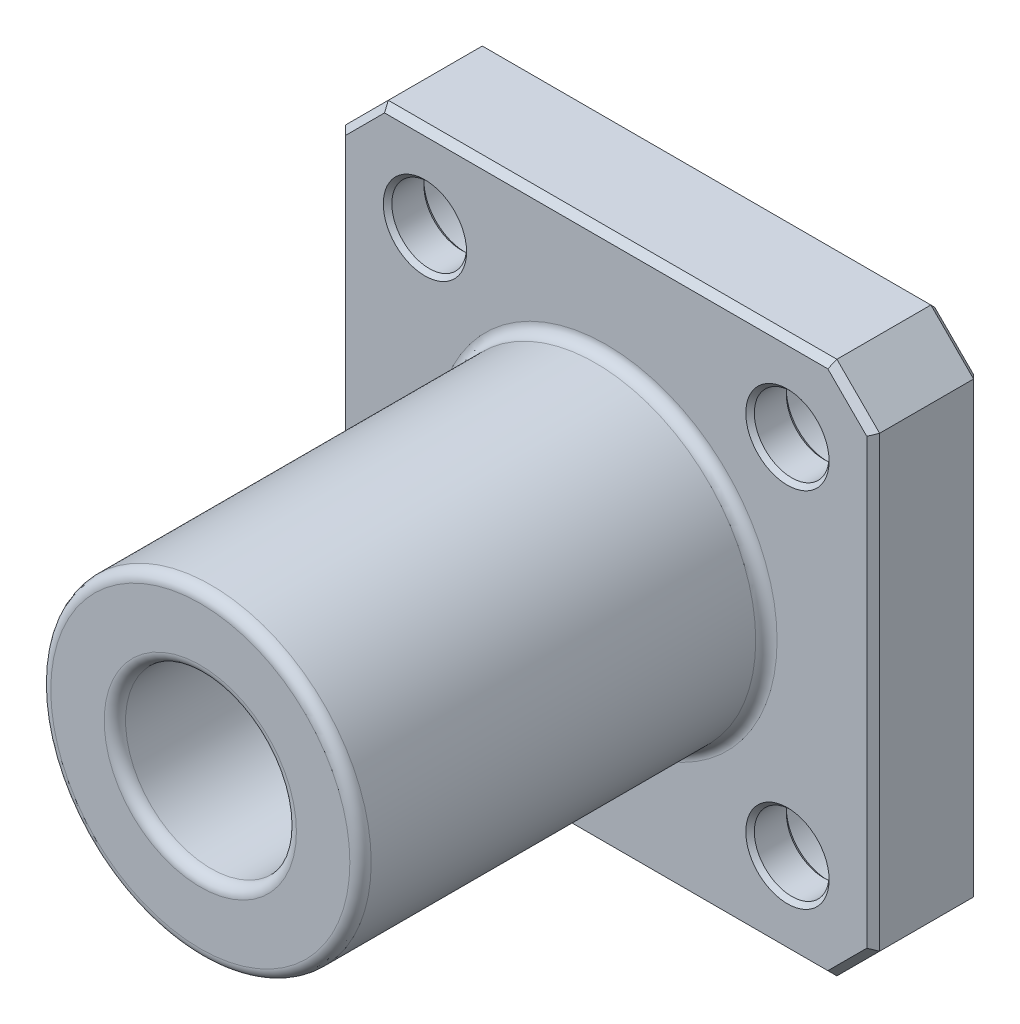
SolidWorks part; units mm, degrees
ref_plane "前视基准面" through (0, 0, 0) normal (0, 0, 1) x (1, 0, 0)
ref_plane "上视基准面" through (0, 0, 0) normal (0, 1, 0) x (1, 0, 0)
ref_plane "右视基准面" through (0, 0, 0) normal (1, 0, 0) x (0, 0, -1)
sketch "Sketch1" plane through (0, 0, 0) normal (0, 0, 1) x (1, 0, 0)
  line L1 (-12.5, 12.5) -> (12.5, 12.5)
  line L2 (-12.5, 12.5) -> (-12.5, -12.5)
  line L3 (-12.5, -12.5) -> (12.5, -12.5)
  line L4 (12.5, 12.5) -> (12.5, -12.5)
  line L5 (-12.5, 12.5) -> (12.5, -12.5) construction
  line L6 (-12.5, -12.5) -> (12.5, 12.5) construction
  circle A0 centre (0, 0) radius 4
  point P0 (0, 0)
  dimension "D2" = 8
  dimension "D1" = 25
extrude "Boss-Extrude1" add sketch "Sketch1" along normal blind 5
sketch "Sketch2" plane through (0, 0, 5) normal (0, 0, 1) x (1, 0, 0)
  circle A0 centre (0, 0) radius 7.5
  circle A1 centre (0, 0) radius 4
  dimension "D1" = 15
extrude "Boss-Extrude2" add sketch "Sketch2" along normal blind 19
chamfer "Chamfer1" distance 2 angle 45 4 edges at (-12.5, 12.5, 2.5) (-12.5, -12.5, 2.5) (12.5, -12.5, 2.5) (12.5, 12.5, 2.5)
sketch "Sketch3" plane through (0, 0, 0) normal (0, 0, -1) x (-1, 0, 0)
  line L0 (0, 0) -> (-11.5, 11.5) construction
  line L1 (-10.5, 12.5) -> (-12.5, 10.5) construction
  circle A0 centre (0, 0) radius 12 construction
  circle A1 centre (-8.4853, 8.4853) radius 1.5
  circle A2 centre (8.4853, 8.4853) radius 1.5
  circle A3 centre (8.4853, -8.4853) radius 1.5
  circle A4 centre (-8.4853, -8.4853) radius 1.5
  point P17 (0, 0)
  dimension "D1" = 24
  dimension "D2" = 3
  dimension "D3" = 4
hole_wizard "CBORE for M3 Pan Head Screw1" positions "3DSketch1" profile "Sketch4" counterbore size "M3" standard "JIS" end condition through all
sketch3d "3DSketch1"
  point P0 (8.4853, 8.4853, 0)
  point P3 (-8.4853, 8.4853, 0)
  point P6 (-8.4853, -8.4853, 0)
  point P9 (8.4853, -8.4853, 0)
sketch "Sketch4" plane through (8.4853, 8.4853, 0) normal (1, 0, 0) x (0, 1, 0)
  line L0 (0, 0) -> (0, 24)
  line L1 (0, 24) -> (1.75, 24)
  line L3 (1.75, 24) -> (1.75, 3.1)
  line L4 (3, 3.1) -> (1.75, 3.1)
  line L5 (3, 3.1) -> (3, 0.525)
  line L6 (3, 0.525) -> (3.525, 0)
  line L7 (3.525, 0) -> (0, 0)
  line L8 (-3, 0.525) -> (-3.525, 0) construction
  line L11 (0, -6.35) -> (0, 107.95) construction
  dimension "Thru Hole Dia." = 3.5
  dimension "Thru Hole Depth" = 24
  dimension "C'Bore Dia." = 6
  dimension "C'Bore Depth" = 3.1
  dimension "Near C'Sink Dia." = 7.05
  dimension "Near C'Sink Angle" = 90
chamfer "Chamfer2" distance 0.3 angle 45 16 edges at (-12.5, 0, 5) (-11.5, -11.5, 5) (0, -12.5, 5) (11.5, -11.5, 5) (12.5, 0, 5) (11.5, 11.5, 5) (0, 12.5, 5) (-11.5, 11.5, 5) (-12.5, 0, 0) (-11.5, -11.5, 0) (0, -12.5, 0) (11.5, -11.5, 0) (12.5, 0, 0) (11.5, 11.5, 0) (0, 12.5, 0) (-11.5, 11.5, 0)
fillet "Fillet1" radius 0.5 1 edges at (7.5, 0, 24)
fillet "Fillet2" radius 0.5 1 edges at (4, 0, 24)
chamfer "Chamfer3" distance 0.3 angle 45 1 edges at (4, 0, 0)
fillet "Fillet3" radius 0.5 1 edges at (7.5, 0, 5)
chamfer "Chamfer4" distance 0.2 angle 45 8 edges at (-10.2353, -8.4853, 3.1) (-6.7353, -8.4853, 5) (-10.2353, 8.4853, 3.1) (-6.7353, 8.4853, 5) (6.7353, 8.4853, 3.1) (10.2353, 8.4853, 5) (6.7353, -8.4853, 3.1) (10.2353, -8.4853, 5)
